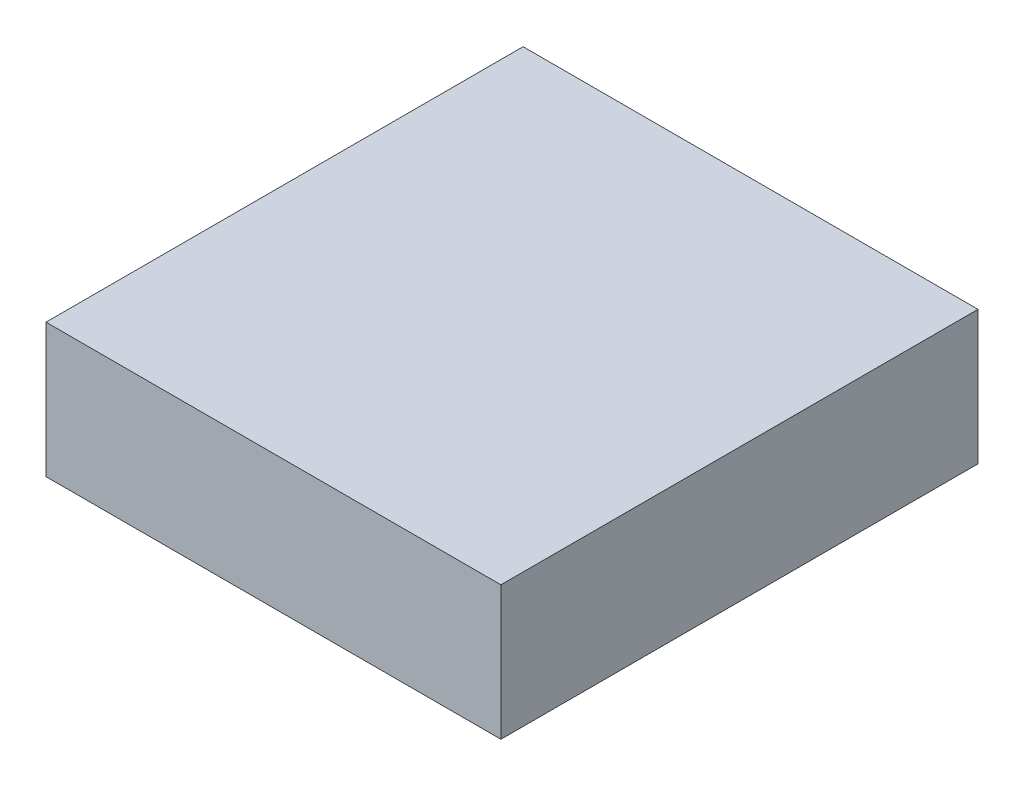
SolidWorks part; units mm, degrees
ref_plane "Front Plane" through (0, 0, 0) normal (0, 0, 1) x (1, 0, 0)
ref_plane "Top Plane" through (0, 0, 0) normal (0, 1, 0) x (1, 0, 0)
ref_plane "Right Plane" through (0, 0, 0) normal (1, 0, 0) x (0, 0, -1)
sketch "Sketch1" plane through (0, 0, 0) normal (0, 1, 0) x (1, 0, 0)
  line L1 (-32.3, -33.875) -> (32.3, -33.875)
  line L2 (-32.3, -33.875) -> (-32.3, 33.875)
  line L3 (-32.3, 33.875) -> (32.3, 33.875)
  line L4 (32.3, -33.875) -> (32.3, 33.875)
  line L5 (-32.3, -33.875) -> (32.3, 33.875) construction
  line L6 (-32.3, 33.875) -> (32.3, -33.875) construction
  point P0 (0, 0)
  dimension "D1" = 64.6
  dimension "D2" = 67.75
extrude "Boss-Extrude1" add sketch "Sketch1" along normal blind 19
